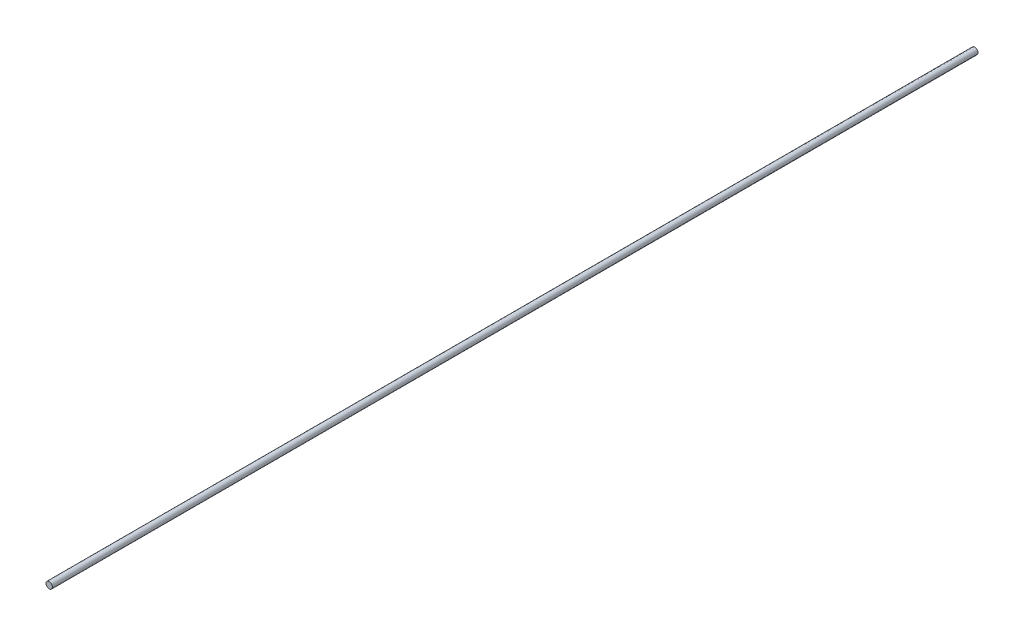
SolidWorks part; units mm, degrees
ref_plane "Front Plane" through (0, 0, 0) normal (0, 0, 1) x (1, 0, 0)
ref_plane "Top Plane" through (0, 0, 0) normal (0, 1, 0) x (1, 0, 0)
ref_plane "Right Plane" through (0, 0, 0) normal (1, 0, 0) x (0, 0, -1)
sketch "Sketch1" plane through (0, 0, 0) normal (0, 0, 1) x (1, 0, 0)
  circle A0 centre (0, 0) radius 7.9375
  dimension "D1" = 15.875
extrude "Boss-Extrude1" add sketch "Sketch1" along normal blind 2286
